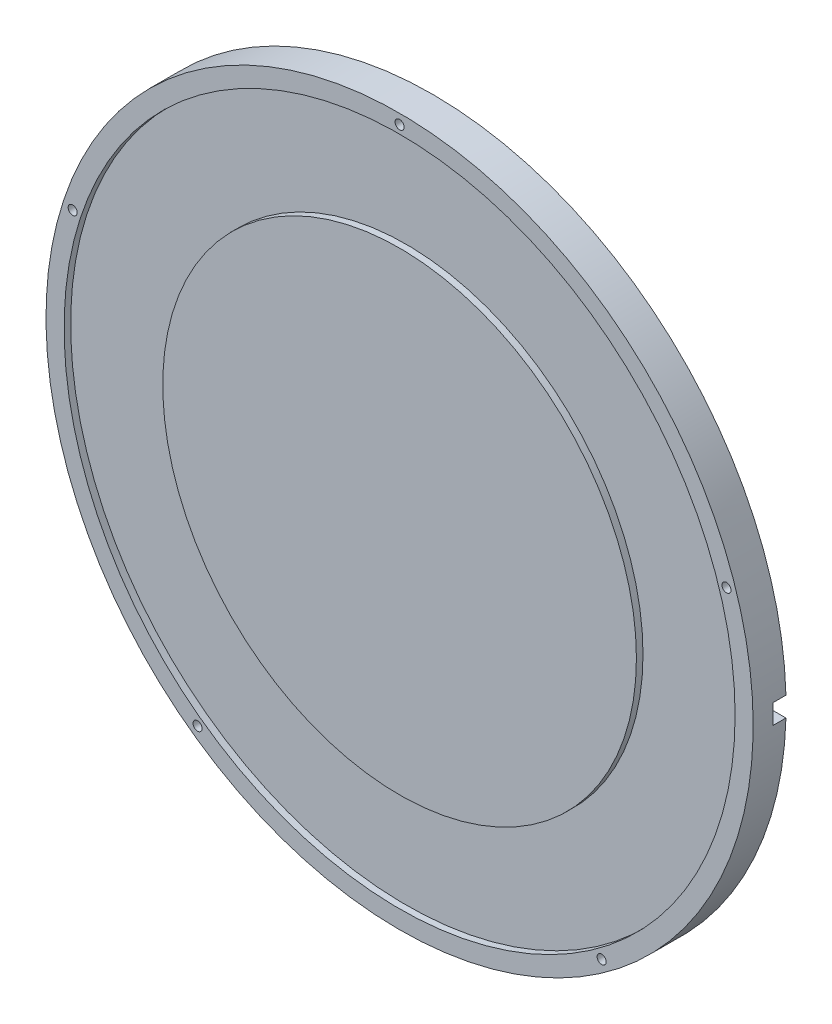
SolidWorks part; units mm, degrees
ref_plane "Front Plane" through (0, 0, 0) normal (0, 0, 1) x (1, 0, 0)
ref_plane "Top Plane" through (0, 0, 0) normal (0, 1, 0) x (1, 0, 0)
ref_plane "Right Plane" through (0, 0, 0) normal (1, 0, 0) x (0, 0, -1)
sketch "Sketch1" plane through (0, 0, 0) normal (0, 0, 1) x (1, 0, 0)
  circle A0 centre (0, 0) radius 215
extrude "Plate" add sketch "Sketch1" along normal blind 20
ref_plane "Plane_z16" through (0, 0, 16) normal (0, 0, 1) x (1, 0, 0)
sketch "Sketch2" plane through (0, 0, 16) normal (0, 0, 1) x (1, 0, 0)
  circle A0 centre (0, 0) radius 204
  circle A1 centre (0, 0) radius 144
extrude "Comb_groove" cut sketch "Sketch2" along normal blind 4
sketch "Sketch3" plane through (0, 0, 0) normal (0, 0, 1) x (1, 0, 0)
  circle A0 centre (198.7708, 64.5846) radius 2.75
  circle A1 centre (0, 209) radius 2.75
  circle A2 centre (-198.7708, 64.5846) radius 2.75
  circle A3 centre (-122.8471, -169.0846) radius 2.75
  circle A4 centre (122.8471, -169.0846) radius 2.75
extrude "Rod_holes" cut sketch "Sketch3" along normal blind 20
sketch "Sketch4" plane through (0, 0, 0) normal (0, 0, 1) x (1, 0, 0)
  circle A0 centre (198.7708, 64.5846) radius 5
  circle A1 centre (0, 209) radius 5
  circle A2 centre (-198.7708, 64.5846) radius 5
  circle A3 centre (-122.8471, -169.0846) radius 5
  circle A4 centre (122.8471, -169.0846) radius 5
extrude "Nut_pockets" cut sketch "Sketch4" along normal blind 6
sketch "Sketch5" plane through (0, 0, 0) normal (0, 0, 1) x (1, 0, 0)
  line L1 (125, -15) -> (165, -15)
  line L2 (125, -15) -> (125, 15)
  line L3 (125, 15) -> (165, 15)
  line L4 (165, -15) -> (165, 15)
extrude "PD_pocket" cut sketch "Sketch5" along normal blind 8
sketch "Sketch6" plane through (0, 0, 0) normal (0, 0, 1) x (1, 0, 0)
  line L1 (160, -6) -> (220, -6)
  line L2 (160, -6) -> (160, 6)
  line L3 (160, 6) -> (220, 6)
  line L4 (220, -6) -> (220, 6)
extrude "Cable_channel" cut sketch "Sketch6" along normal blind 8
